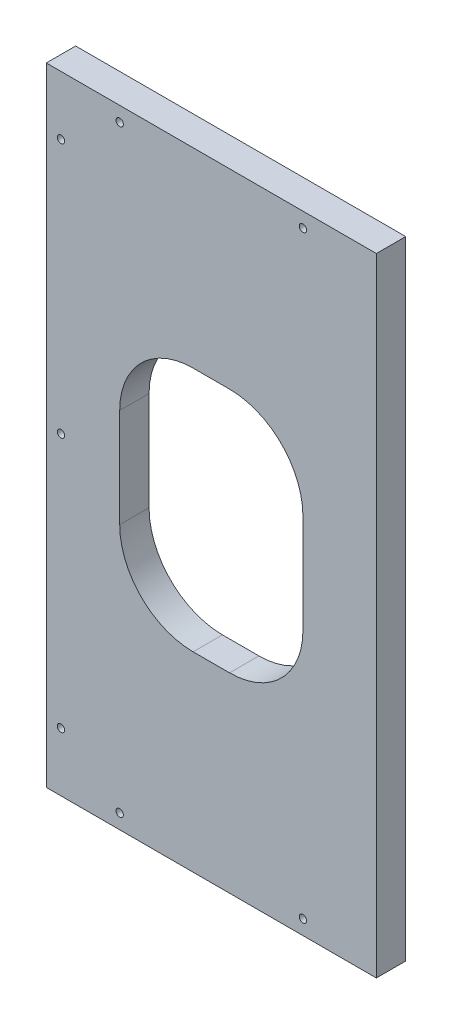
SolidWorks part; units mm, degrees
material "Beech"
ref_plane "Front Plane" through (0, 0, 0) normal (0, 0, 1) x (1, 0, 0)
ref_plane "Top Plane" through (0, 0, 0) normal (0, 1, 0) x (1, 0, 0)
ref_plane "Right Plane" through (0, 0, 0) normal (1, 0, 0) x (0, 0, -1)
sketch "Sketch1" plane through (0, 0, 0) normal (0, 0, 1) x (1, 0, 0)
  line L0 (-234.753, 19.05) -> (-234.753, 0) construction
  line L1 (-234.753, 82.8417) -> (-91.9973, 82.8417)
  line L2 (-234.753, 82.8417) -> (-234.753, -188.5238)
  line L3 (-234.753, -188.5238) -> (-91.9973, -188.5238)
  line L4 (-91.9973, 82.8417) -> (-91.9973, -188.5238)
extrude "Boss-Extrude1" add sketch "Sketch1" along normal blind 12.7
hole_wizard "Hole1" positions "Sketch2" profile "Sketch3" legacy
sketch "Sketch2" plane through (181.0394, -52.975, 0) normal (0, 0, -1) x (0, -1, 0)
  line L0 (-129.4667, 415.7924) -> (-129.4667, 273.0368) construction
  line L5 (-135.8167, 409.4424) -> (135.5488, 409.4424) construction
  line L10 (-135.8167, 279.3868) -> (135.5488, 279.3868) construction
  line L11 (-0.134, 409.4424) -> (-0.134, 279.3868) construction
  point P22 (-129.4667, 384.0424)
  point P24 (-129.4667, 304.7868)
  point P26 (-110.4167, 409.4424)
  point P30 (-0.134, 409.4424)
  point P50 (110.1488, 409.4424)
  point P51 (129.1988, 304.7868)
  point P52 (129.1988, 384.0424)
sketch "Sketch3" plane through (-203.003, -182.1738, 0) normal (1, 0, 0) x (0, 1, 0)
  line L0 (0, 0) -> (0, 32.7039)
  line L1 (0, 32.7039) -> (1.5875, 31.75)
  line L2 (1.5875, 31.75) -> (1.5875, 4.0177)
  line L3 (1.5875, 4.0177) -> (5.08, 0)
  line L4 (5.08, 0) -> (0, 0)
  line L5 (0, -14.3089) -> (0, 102.4216) construction
  line L6 (0, 32.7039) -> (-1.5875, 31.75) construction
  line L7 (-1.5875, 4.0177) -> (-5.08, 0) construction
  dimension "Diameter" = 3.175
  dimension "Depth" = 31.75
  dimension "C-Sink Diameter" = 10.16
  dimension "C-Sink Angle" = 82
  dimension "Drill Angle" = 118
chamfer "Chamfer1" [suppressed] distance 3.175 angle 45
sketch "Sketch4" plane through (0, 0, 12.7) normal (0, 0, 1) x (1, 0, 0)
  line L0 (-234.753, -52.841) -> (-91.9973, -52.841) construction
  line L6 (-234.753, 82.8417) -> (-234.753, -188.5238) construction
  line L7 (-91.9973, -188.5238) -> (-91.9973, 82.8417) construction
  line L8 (-234.753, 82.8417) -> (-234.753, -188.5238) construction
  line L16 (-123.7473, -105.9738) -> (-203.003, -105.9738)
  line L17 (-123.7473, -105.9738) -> (-123.7473, 0.2917)
  line L18 (-123.7473, 0.2917) -> (-203.003, 0.2917)
  line L19 (-203.003, -105.9738) -> (-203.003, 0.2917)
  line L20 (-123.7473, -105.9738) -> (-203.003, 0.2917) construction
  line L21 (-123.7473, 0.2917) -> (-203.003, -105.9738) construction
  line L22 (-91.9973, 82.8417) -> (-234.753, 82.8417) construction
  point P9 (-163.3751, -52.841)
  dimension "D2" = 82.55
  dimension "D1" = 31.75
extrude "Cut-Extrude1" cut sketch "Sketch4" against normal through all
fillet "Fillet1" radius 31.75 4 edges at (-123.7473, -105.9738, 6.35) (-123.7473, 0.2917, 6.35) (-203.003, 0.2917, 6.35) (-203.003, -105.9738, 6.35)
